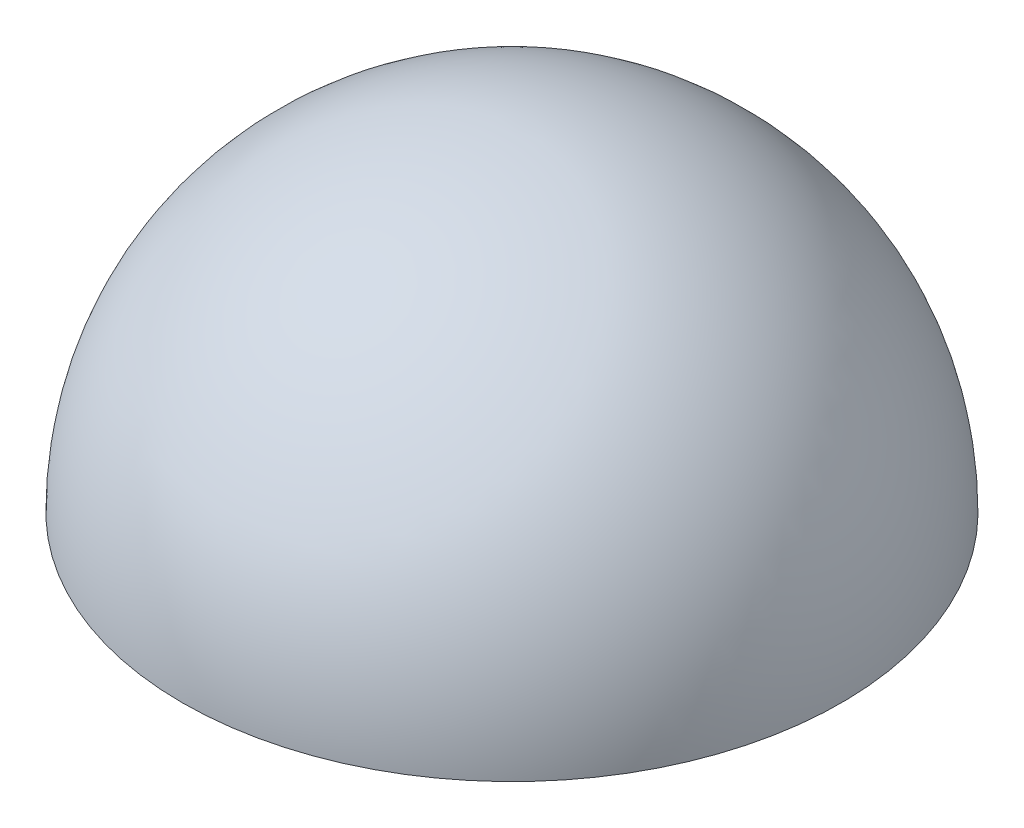
SolidWorks part; units mm, degrees
material "Silicon Rubber"
ref_plane "Front" through (0, 0, 0) normal (0, 0, 1) x (1, 0, 0)
ref_plane "Top" through (0, 0, 0) normal (0, 1, 0) x (1, 0, 0)
ref_plane "Right" through (0, 0, 0) normal (1, 0, 0) x (0, 0, -1)
sketch "Sketch4" plane through (0, 0, 0) normal (0, 1, 0) x (1, 0, 0)
  line L0 (0, 0) -> (50, 0)
  arc A0 (0, 0) -> (50, 0) centre (25, 0) cw
  dimension "D2" = 25
  dimension "D1" = 50
revolve "Revolve1" add sketch "Sketch4" angle 180 about L0
